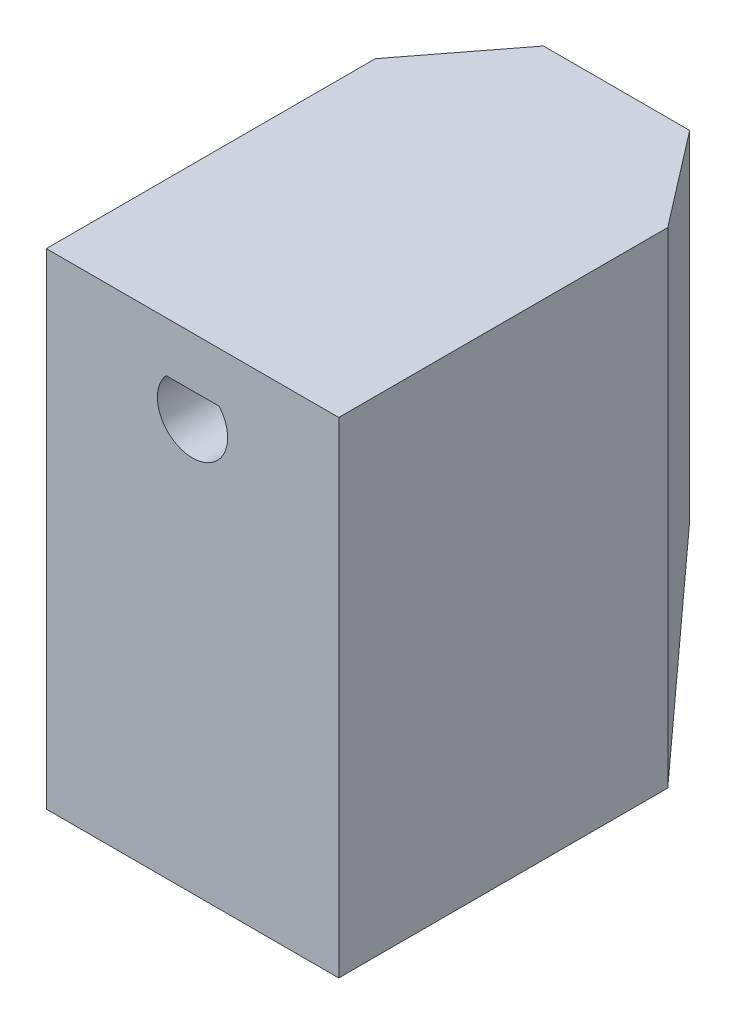
SolidWorks part; units mm, degrees
ref_plane "Front Plane" through (0, 0, 0) normal (0, 0, 1) x (1, 0, 0)
ref_plane "Top Plane" through (0, 0, 0) normal (0, 1, 0) x (1, 0, 0)
ref_plane "Right Plane" through (0, 0, 0) normal (1, 0, 0) x (0, 0, -1)
sketch "Sketch2" plane through (0, 0, 0) normal (0, 0, 1) x (1, 0, 0)
  line L0 (12.7, -6.35) -> (14.2875, -6.35)
  line L1 (-14.2875, 6.35) -> (14.2875, 6.35)
  line L2 (-14.2875, 6.35) -> (-14.2875, -6.35)
  line L3 (-14.2875, -6.35) -> (-12.7, -6.35)
  line L4 (14.2875, 6.35) -> (14.2875, -6.35)
  line L6 (-12.7, -6.35) -> (-12.7, -35.814)
  line L7 (-12.7, -35.814) -> (12.7, -35.814)
  line L8 (12.7, -6.35) -> (12.7, -35.814)
  point P4 (-9.5161, -73.0851)
  point P5 (0, 6.35)
  point P7 (14.2875, 0)
  point P8 (9.8122, -26.939)
  point P13 (0, -35.814)
  point P14 (6.9696, -15.0139)
  point P15 (14.395, -15.3427)
  point P16 (8.6078, -36.35)
  dimension "D1" = 28.575
  dimension "D2" = 12.7
  dimension "D3" = 42.164
  dimension "D4" = 25.4
extrude "Boss-Extrude1" add sketch "Sketch2" along normal blind 25.4 contours L4 L1 L2 L3 | L8 L3 L6 L7
sketch "Sketch3" plane through (0, 0, 25.4) normal (0, 0, 1) x (1, 0, 0)
  line L0 (-2.3, 2.0031) -> (2.3, 2.0031)
  arc A0 (-2.3, 2.0031) -> (2.3, 2.0031) centre (0, 0) ccw
  dimension "D1" = 6.1
  dimension "D2" = 4.6
extrude "Cut-Extrude1" cut sketch "Sketch3" against normal blind 9.5
sketch "Sketch5" plane through (0, 0, 0) normal (0, 0, -1) x (-1, 0, 0)
  line L0 (14.2875, 6.35) -> (-14.2875, 6.35) construction
  line L1 (-12.7, 6.35) -> (12.7, 6.35)
  line L2 (-12.7, 6.35) -> (-12.7, -35.814)
  line L3 (-12.7, -35.814) -> (12.7, -35.814)
  line L4 (12.7, 6.35) -> (12.7, -35.814)
  line L5 (12.7, -6.35) -> (12.7, -35.814) construction
  line L6 (-12.7, -6.35) -> (-12.7, -35.814) construction
  point P6 (7.5, -24.3735)
  point P9 (-7.5, -20.2012)
  dimension "D1" = 42.164
extrude "Boss-Extrude2" add sketch "Sketch5" along normal blind 11.43
sketch "Sketch6" plane through (12.7, 0, 0) normal (1, 0, 0) x (0, 0, -1)
  line L0 (3.175, -35.814) -> (11.43, -23.0188)
  line L1 (-25.4, -35.814) -> (11.43, -35.814) construction
  line L2 (11.43, 6.35) -> (11.43, -35.814) construction
  line L3 (11.43, -23.0188) -> (11.43, -35.814)
  line L4 (11.43, -35.814) -> (3.175, -35.814)
  point P6 (0, 0)
  dimension "D1" = 3.175
  dimension "D2" = 23.0188
extrude "Cut-Extrude2" cut sketch "Sketch6" against normal up to next
sketch "Sketch7" plane through (0, -35.814, 0) normal (0, -1, 0) x (1, 0, 0)
  line L0 (-12.7, -11.43) -> (-12.7, -3.175)
  line L1 (-12.7, -3.175) -> (-6.35, -11.43)
  line L2 (-12.7, -11.43) -> (12.7, -11.43) construction
  line L3 (-6.35, -11.43) -> (-12.7, -11.43)
  line L4 (6.35, -11.43) -> (12.7, -3.175)
  line L5 (12.7, -3.175) -> (12.7, -11.43)
  line L6 (12.7, -11.43) -> (6.35, -11.43)
  line L7 (-6.35, -11.43) -> (6.35, -11.43) construction
  point P10 (0, -11.43)
  dimension "D1" = 12.7
extrude "Cut-Extrude3" cut sketch "Sketch7" against normal up to next
sketch "Sketch8" plane through (0, 0, -11.43) normal (0, 0, -1) x (-1, 0, 0)
  line L0 (-1.651, 2.8596) -> (1.651, 2.8596)
  arc A0 (-1.651, 2.8596) -> (1.651, 2.8596) centre (0, 0) ccw
  dimension "D1" = 6.604
  dimension "D2" = 3.302
extrude "Cut-Extrude4" cut sketch "Sketch8" against normal blind 20
sketch "Sketch10" plane through (0, -35.814, 0) normal (0, -1, 0) x (1, 0, 0)
  line L0 (-12.7, 25.4) -> (12.7, 25.4) construction
  line L1 (-9.525, 22.225) -> (9.525, 22.225)
  line L2 (-9.525, 22.225) -> (-9.525, 3.175)
  line L3 (-9.525, 3.175) -> (9.525, 3.175)
  line L4 (9.525, 22.225) -> (9.525, 3.175)
  line L5 (12.7, 25.4) -> (12.7, -3.175) construction
  line L6 (12.7, 0) -> (14.2875, 0) construction
  point P6 (0, 22.225)
  dimension "D1" = 3.175
  dimension "D2" = 3.175
  dimension "D3" = 3.175
extrude "Cut-Extrude5" cut sketch "Sketch10" against normal offset from surface (26.289 mm away) 3.175 up to face at (13.4938, -6.35, 12.7)
sketch "Sketch11" plane through (0, 0, 25.4) normal (0, 0, 1) x (1, 0, 0)
  line L1 (-14.2875, 6.35) -> (-12.7, 6.35)
  line L2 (-14.2875, 6.35) -> (-14.2875, -6.35)
  line L3 (-14.2875, -6.35) -> (-12.7, -6.35)
  line L4 (-12.7, 6.35) -> (-12.7, -6.35)
  line L5 (12.7, -6.35) -> (14.2875, -6.35)
  line L6 (12.7, -6.35) -> (12.7, 6.35)
  line L7 (12.7, 6.35) -> (14.2875, 6.35)
  line L8 (14.2875, -6.35) -> (14.2875, 6.35)
extrude "Cut-Extrude6" cut sketch "Sketch11" against normal up to next
